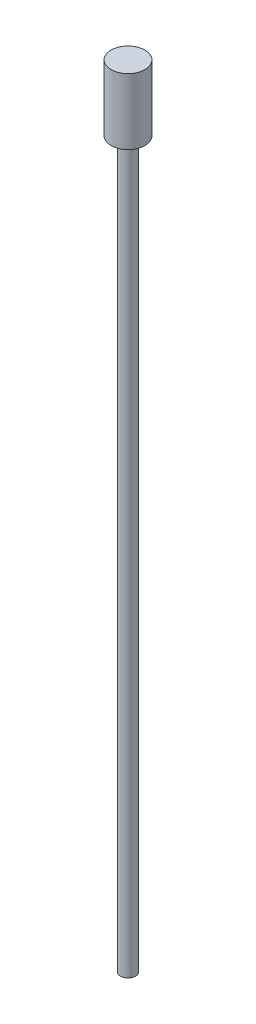
SolidWorks part; units mm, degrees
ref_plane "Plan de face" through (0, 0, 0) normal (0, 0, 1) x (1, 0, 0)
ref_plane "Plan de dessus" through (0, 0, 0) normal (0, 1, 0) x (1, 0, 0)
ref_plane "Plan de droite" through (0, 0, 0) normal (1, 0, 0) x (0, 0, -1)
sketch "Esquisse1" plane through (0, 0, 0) normal (0, 1, 0) x (1, 0, 0)
  circle A0 centre (0, 0) radius 4
  dimension "D1" = 8
extrude "Boss.-Extru.1" add sketch "Esquisse1" along normal blind 385
sketch "Esquisse2" plane through (0, 385, 0) normal (0, 1, 0) x (1, 0, 0)
  circle A0 centre (0, 0) radius 9
  dimension "D1" = 18
extrude "Boss.-Extru.2" add sketch "Esquisse2" along normal blind 35
